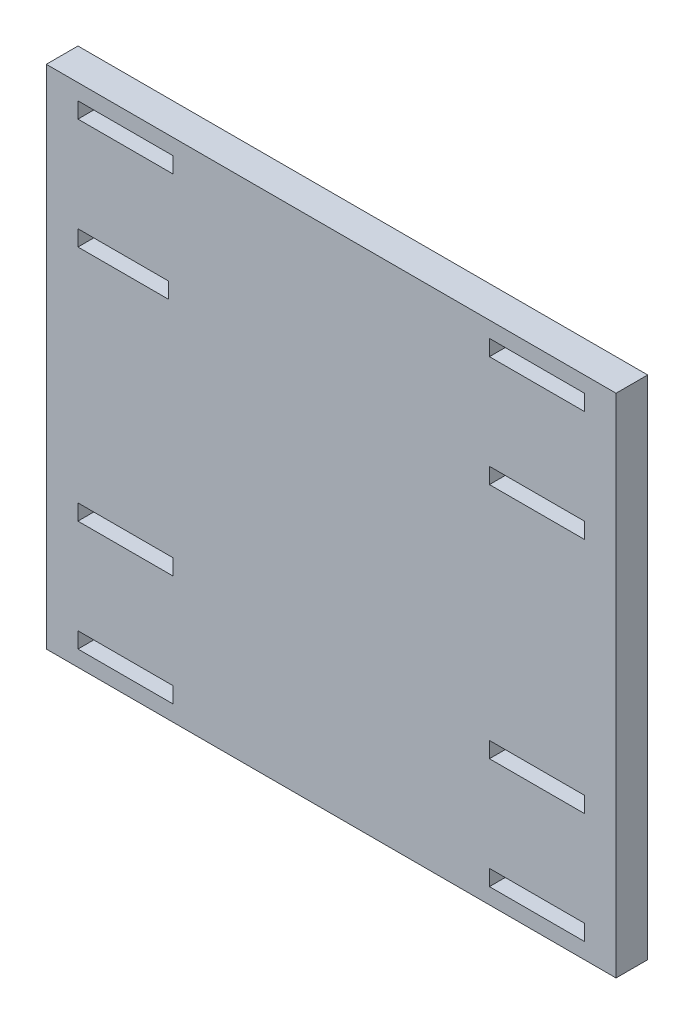
SolidWorks part; units mm, degrees
ref_plane "Front Plane" through (0, 0, 0) normal (0, 0, 1) x (1, 0, 0)
ref_plane "Top Plane" through (0, 0, 0) normal (0, 1, 0) x (1, 0, 0)
ref_plane "Right Plane" through (0, 0, 0) normal (1, 0, 0) x (0, 0, -1)
sketch "Sketch1" plane through (0, 0, 0) normal (0, 0, 1) x (1, 0, 0)
  line L1 (-90, 80) -> (90, 80)
  line L2 (-90, 80) -> (-90, -80)
  line L3 (-90, -80) -> (90, -80)
  line L4 (90, 80) -> (90, -80)
  line L5 (-90, 80) -> (90, -80) construction
  line L6 (-90, -80) -> (90, 80) construction
  point P0 (0, 0)
extrude "Boss-Extrude1" add sketch "Sketch1" along normal blind 10
sketch "Sketch2" plane through (0, 0, 10) normal (0, 0, 1) x (1, 0, 0)
  line L0 (90, 80) -> (-90, 80) construction
  line L1 (-80, 75) -> (-50, 75)
  line L2 (-80, 75) -> (-80, 70)
  line L3 (-80, 70) -> (-50, 70)
  line L4 (-50, 75) -> (-50, 70)
  line L5 (-80, 75) -> (-50, 70) construction
  line L6 (-80, 70) -> (-50, 75) construction
  line L7 (50, 75) -> (80, 75)
  line L8 (50, 75) -> (50, 70)
  line L9 (50, 70) -> (80, 70)
  line L10 (80, 75) -> (80, 70)
  line L11 (50, 75) -> (80, 70) construction
  line L12 (50, 70) -> (80, 75) construction
  line L13 (-80, 40) -> (-51.4716, 40)
  line L14 (-80, 40) -> (-80, 35)
  line L15 (-80, 35) -> (-51.4716, 35)
  line L16 (-51.4716, 40) -> (-51.4716, 35)
  line L17 (-80, 40) -> (-51.4716, 35) construction
  line L18 (-80, 35) -> (-51.4716, 40) construction
  line L19 (50, 40) -> (80, 40)
  line L20 (50, 40) -> (50, 35)
  line L21 (50, 35) -> (80, 35)
  line L22 (80, 40) -> (80, 35)
  line L23 (50, 40) -> (80, 35) construction
  line L24 (50, 35) -> (80, 40) construction
  line L25 (-80, -35) -> (-50, -35)
  line L26 (-80, -35) -> (-80, -40)
  line L27 (-80, -40) -> (-50, -40)
  line L28 (-50, -35) -> (-50, -40)
  line L29 (-80, -35) -> (-50, -40) construction
  line L30 (-80, -40) -> (-50, -35) construction
  line L31 (50, -35) -> (80, -35)
  line L32 (50, -35) -> (50, -40)
  line L33 (50, -40) -> (80, -40)
  line L34 (80, -35) -> (80, -40)
  line L35 (50, -35) -> (80, -40) construction
  line L36 (50, -40) -> (80, -35) construction
  line L37 (-80, -70) -> (-50, -70)
  line L38 (-80, -70) -> (-80, -75)
  line L39 (-80, -75) -> (-50, -75)
  line L40 (-50, -70) -> (-50, -75)
  line L41 (-80, -70) -> (-50, -75) construction
  line L42 (-80, -75) -> (-50, -70) construction
  line L43 (50, -70) -> (80, -70)
  line L44 (50, -70) -> (50, -75)
  line L45 (50, -75) -> (80, -75)
  line L46 (80, -70) -> (80, -75)
  line L47 (50, -70) -> (80, -75) construction
  line L48 (50, -75) -> (80, -70) construction
  line L49 (-90, 80) -> (-90, -80) construction
  line L50 (90, -80) -> (90, 80) construction
  line L51 (-90, -80) -> (90, -80) construction
  point P0 (-65, 72.5)
  point P5 (65, 72.5)
  point P10 (-65.7358, 37.5)
  point P15 (65, 37.5)
  point P20 (-65, -37.5)
  point P25 (65, -37.5)
  point P30 (-65, -72.5)
  point P35 (65, -72.5)
  point P42 (-80, 72.5)
  point P49 (0, 0)
  point P50 (0, 0)
  dimension "D1" = 30
  dimension "D2" = 5
  dimension "D3" = 10
  dimension "D4" = 10
  dimension "D5" = 5
  dimension "D6" = 30
  dimension "D7" = 30
  dimension "D8" = 30
  dimension "D9" = 30
extrude "Cut-Extrude2" cut sketch "Sketch2" against normal through all
